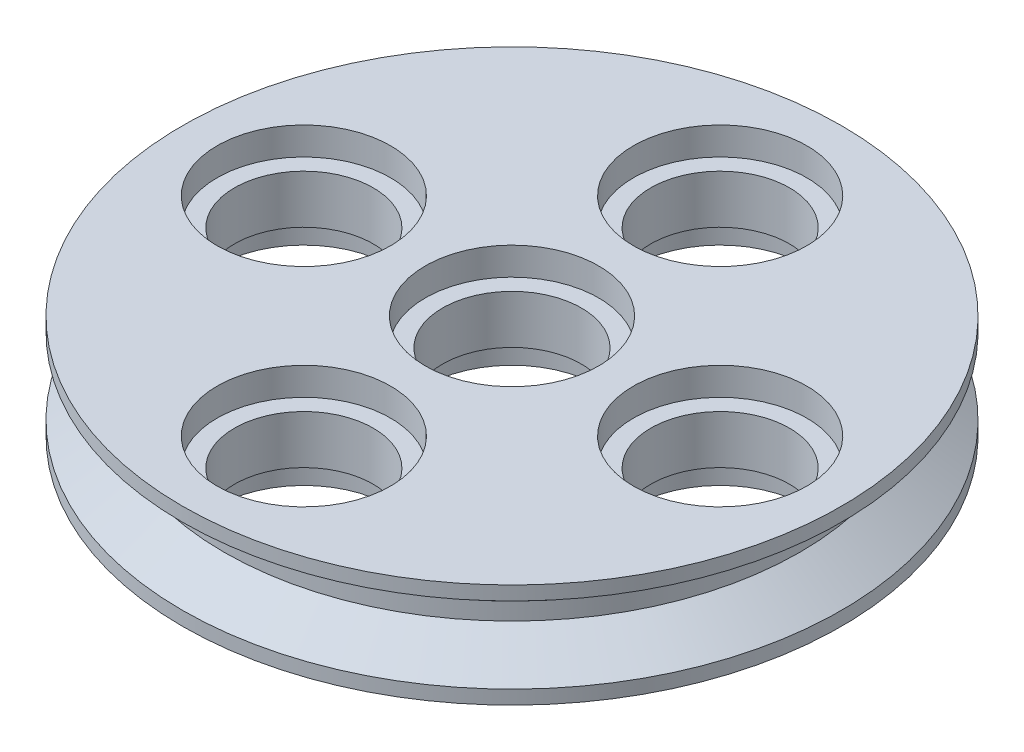
SolidWorks part; units mm, degrees
ref_plane "Plan de face" through (0, 0, 0) normal (0, 0, 1) x (1, 0, 0)
ref_plane "Plan de dessus" through (0, 0, 0) normal (0, 1, 0) x (1, 0, 0)
ref_plane "Plan de droite" through (0, 0, 0) normal (1, 0, 0) x (0, 0, -1)
sketch "Sketch1" plane through (0, 0, 0) normal (0, 0, 1) x (1, 0, 0)
  line L0 (0, 0) -> (0, 1.5)
  line L1 (0, 1.5) -> (-9.5, 1.5)
  line L2 (-8.3007, 0) -> (-8.3007, 0.25)
  line L3 (-8.3007, 0.25) -> (-9.5, 1.1)
  line L4 (-9.5, 1.1) -> (-9.5, 1.5)
  line L5 (-8.3007, 0) -> (0, 0)
  dimension "D1" = 9.5
  dimension "D2" = 1.47
  dimension "D3" = 0.25
  dimension "D4" = 0.4
  dimension "D5" = 1.5
revolve "Revolve1" add sketch "Sketch1" angle 360 about L0
hole_wizard "Hole1" positions "Sketch3" profile "Sketch2" legacy end condition through all
sketch "Sketch3" plane through (0, 1.5, 0) normal (0, 1, 0) x (1, 0, 0)
  point P0 (0, 0)
  point P3 (0, 6)
  point P5 (-6, 0)
  point P7 (0, -6)
  point P9 (6, 0)
  dimension "D1" = 6
  dimension "D2" = 6
  dimension "D3" = 6
  dimension "D4" = 6
sketch "Sketch2" plane through (0, 1.5, 0) normal (1, 0, 0) x (0, 0, 1)
  line L0 (0, 0) -> (0, 2.7017)
  line L1 (0, 2.7017) -> (2, 1.5)
  line L2 (2, 1.5) -> (2, 0.8)
  line L3 (2, 0.8) -> (2.5, 0.8)
  line L4 (2.5, 0) -> (0, 0)
  line L5 (0, -11.3109) -> (0, 121.1557) construction
  line L6 (0, 2.7017) -> (-2, 1.5) construction
  line L7 (2.5, 0.8) -> (2.5, 0)
  dimension "Depth" = 1.5
  dimension "Drill Angle" = 118
  dimension "Diameter" = 4
  dimension "C-Bore Diameter" = 5
  dimension "C-Bore Depth" = 0.8
mirror "Mirror1" about plane through (0, 0, 0) normal (0, 1, 0) of bodies 102
equation "\"D2@Sketch3\"=\"D1@Sketch3\""
equation "\"D3@Sketch3\"=\"D1@Sketch3\""
equation "\"D4@Sketch3\"=\"D1@Sketch3\""
